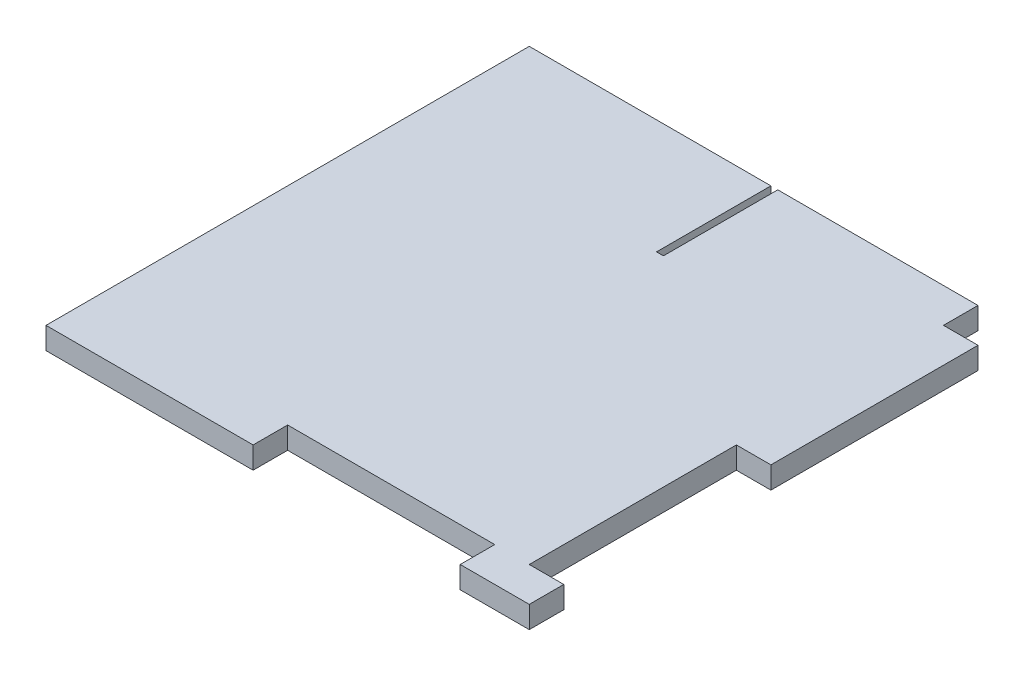
SolidWorks part; units mm, degrees
ref_plane "Front Plane" through (0, 0, 0) normal (0, 0, 1) x (1, 0, 0)
ref_plane "Top Plane" through (0, 0, 0) normal (0, 1, 0) x (1, 0, 0)
ref_plane "Right Plane" through (0, 0, 0) normal (1, 0, 0) x (0, 0, -1)
sketch "Sketch1" plane through (0, 0, 0) normal (0, 1, 0) x (1, 0, 0)
  line L1 (-35, -35) -> (35, -35)
  line L2 (-35, -35) -> (-35, 35)
  line L3 (-35, 35) -> (35, 35)
  line L4 (35, -35) -> (35, 35)
  line L5 (-35, -35) -> (35, 35) construction
  line L6 (-35, 35) -> (35, -35) construction
  point P1 (0, 0)
  dimension "D1" = 70
  dimension "D2" = 70
extrude "Boss-Extrude1" add sketch "Sketch1" along normal blind 3.175
sketch "Sketch2" plane through (0, 3.175, 0) normal (0, 1, 0) x (1, 0, 0)
  line L0 (35, 35) -> (-35, 35) construction
  line L1 (0, 35) -> (1, 35)
  line L2 (0, 35) -> (0, 18.4363)
  line L3 (0, 18.4363) -> (1, 18.4363)
  line L4 (1, 35) -> (1, 18.4363)
  dimension "D1" = 1
extrude "Cut-Extrude1" cut sketch "Sketch2" against normal blind 3.175
sketch "Sketch3" plane through (0, 3.175, 0) normal (0, 1, 0) x (1, 0, 0)
  line L0 (35, -35) -> (35, 35) construction
  line L1 (-35, -35) -> (-5, -35)
  line L2 (-35, -35) -> (-35, -30)
  line L3 (-35, -30) -> (-5, -30)
  line L4 (-5, -35) -> (-5, -30)
  line L5 (-5, -35) -> (25, -35)
  line L6 (-5, -35) -> (-5, -30)
  line L7 (-5, -30) -> (25, -30)
  line L8 (25, -35) -> (25, -30)
  line L9 (25, -35) -> (35, -35)
  line L10 (25, -35) -> (25, -30)
  line L11 (25, -30) -> (35, -30)
  line L12 (35, -35) -> (35, -30)
  line L14 (35, -30) -> (30, -30)
  line L15 (35, -30) -> (35, 0)
  line L16 (35, 0) -> (30, 0)
  line L17 (30, -30) -> (30, 0)
  line L18 (35, 0) -> (30, 0)
  line L19 (35, 0) -> (35, 30)
  line L20 (35, 30) -> (30, 30)
  line L21 (30, 0) -> (30, 30)
  line L22 (35, 30) -> (30, 30)
  line L23 (35, 30) -> (35, 35)
  line L24 (35, 35) -> (30, 35)
  line L25 (30, 30) -> (30, 35)
  line M15 (-35, -35) -> (35, -35)
  line M16 (35, -35) -> (35, 35)
  line M17 (35, 35) -> (1, 35)
  dimension "D1" = 30
  dimension "D2" = 30
  dimension "D3" = 30
  dimension "D4" = 5
  dimension "D5" = 5
  dimension "D6" = 30
extrude "Cut-Extrude2" cut sketch "Sketch3" against normal blind 10 contours L8 L7 L4 M15 | L17 L11 L16 M16 | L25 L20 M16 M17
